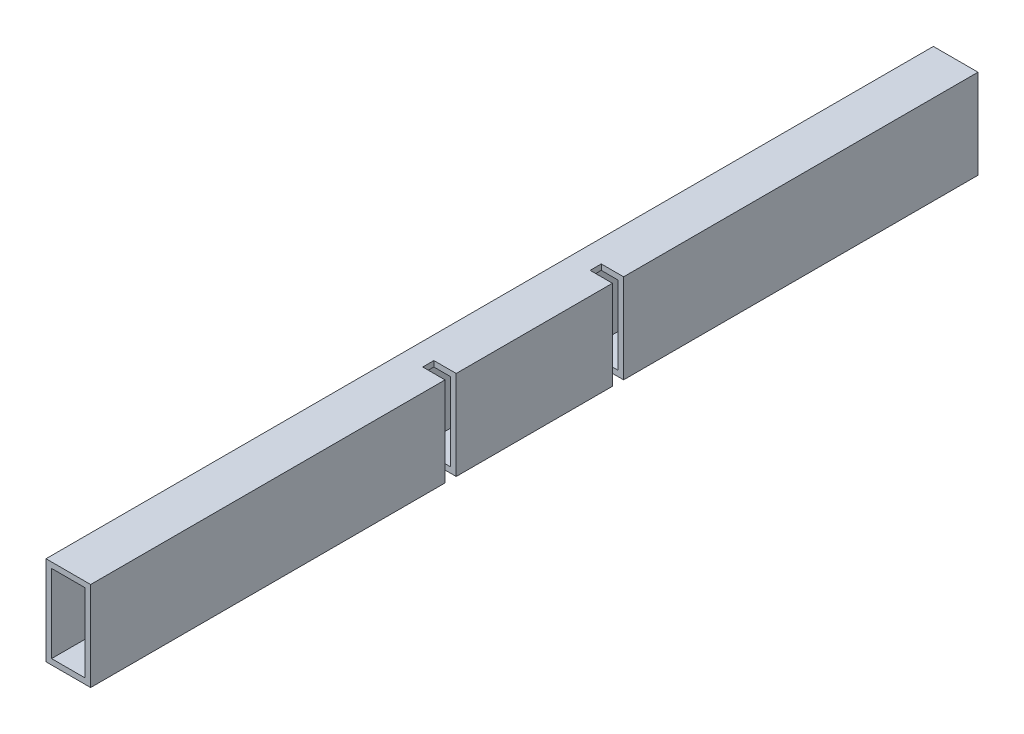
SolidWorks part; units mm, degrees
material "6061-T4 (SS)"
ref_plane "Front Plane" through (0, 0, 0) normal (0, 0, 1) x (1, 0, 0)
ref_plane "Top Plane" through (0, 0, 0) normal (0, 1, 0) x (1, 0, 0)
ref_plane "Right Plane" through (0, 0, 0) normal (1, 0, 0) x (0, 0, -1)
sketch "Sketch1" plane through (0, 0, 0) normal (0, 0, 1) x (1, 0, 0)
  line L0 (-9.525, 22.225) -> (9.525, 22.225)
  line L1 (-12.7, 25.4) -> (12.7, 25.4)
  line L2 (-12.7, 25.4) -> (-12.7, -25.4)
  line L3 (-12.7, -25.4) -> (12.7, -25.4)
  line L4 (12.7, 25.4) -> (12.7, -25.4)
  line L5 (-12.7, 25.4) -> (12.7, -25.4) construction
  line L6 (-12.7, -25.4) -> (12.7, 25.4) construction
  line L7 (9.525, 22.225) -> (9.525, -22.225)
  line L8 (-9.525, -22.225) -> (9.525, -22.225)
  line L9 (-9.525, 22.225) -> (-9.525, -22.225)
  point P0 (0, 0)
  dimension "D1" = 50.8
  dimension "D2" = 25.4
  dimension "D3" = 3.175
extrude "Boss-Extrude1" add sketch "Sketch1" along normal mid plane 504.952
sketch "Sketch2" plane through (12.7, 0, 0) normal (1, 0, 0) x (0, 0, -1)
  line L0 (44.45, 25.4) -> (44.45, -25.4)
  line L1 (-252.476, 25.4) -> (252.476, 25.4) construction
  line L2 (-252.476, -25.4) -> (252.476, -25.4) construction
  line L3 (44.45, -25.4) -> (50.8, -25.4)
  line L4 (50.8, -25.4) -> (50.8, 25.4)
  line L5 (50.8, 25.4) -> (44.45, 25.4)
  line L6 (252.476, -25.4) -> (252.476, 25.4) construction
  line L7 (0, 25.4) -> (0, -31.9106) construction
  line L8 (-50.8, 25.4) -> (-44.45, 25.4)
  line L9 (-50.8, -25.4) -> (-50.8, 25.4)
  line L10 (-44.45, -25.4) -> (-50.8, -25.4)
  line L11 (-44.45, 25.4) -> (-44.45, -25.4)
  dimension "D1" = 201.676
  dimension "D2" = 6.35
extrude "Cut-Extrude1" cut sketch "Sketch2" against normal blind 12.7
